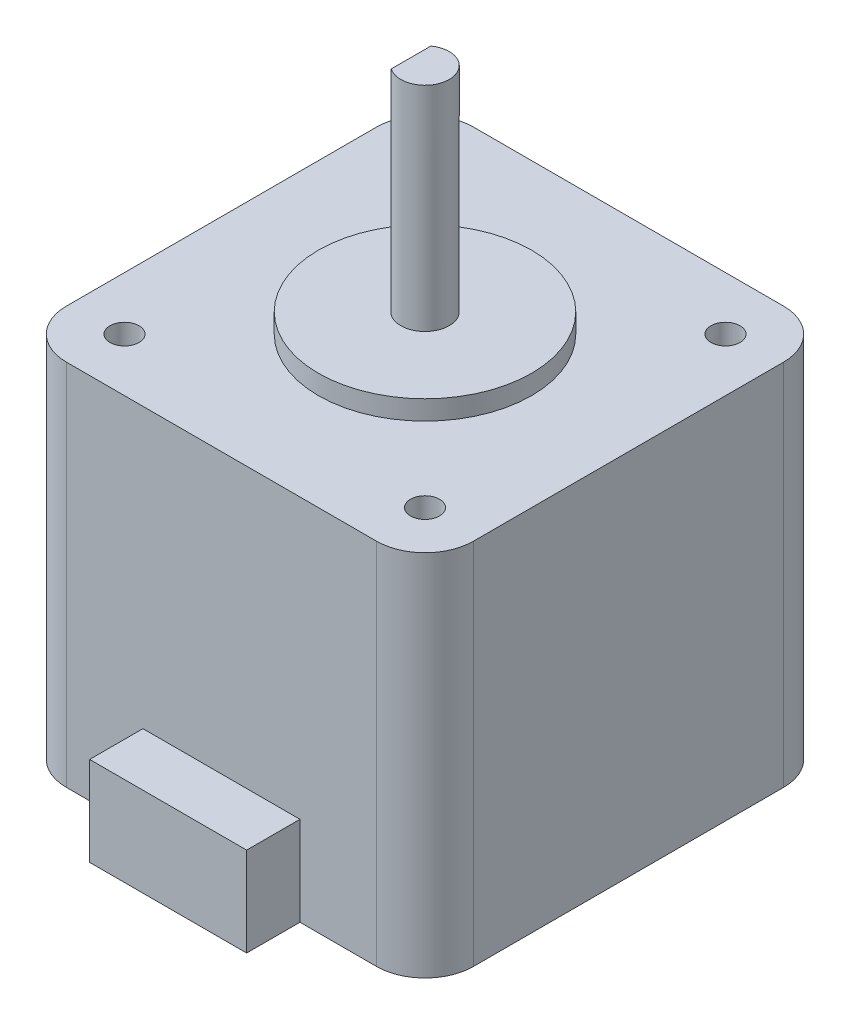
SolidWorks part; units mm, degrees
ref_plane "前视基准面" through (0, 0, 0) normal (0, 0, 1) x (1, 0, 0)
ref_plane "上视基准面" through (0, 0, 0) normal (0, 1, 0) x (1, 0, 0)
ref_plane "右视基准面" through (0, 0, 0) normal (1, 0, 0) x (0, 0, -1)
sketch "草图1" plane through (0, 0, 0) normal (0, 1, 0) x (1, 0, 0)
  line L1 (-21, 21) -> (21, 21)
  line L2 (-21, 21) -> (-21, -21)
  line L3 (-21, -21) -> (21, -21)
  line L4 (21, 21) -> (21, -21)
  line L5 (-21, 21) -> (21, -21) construction
  line L6 (-21, -21) -> (21, 21) construction
  point P0 (0, 0)
  dimension "D1" = 42
extrude "凸台-拉伸1" add sketch "草图1" along normal blind 38
sketch "草图2" plane through (0, 38, 0) normal (0, 1, 0) x (1, 0, 0)
  circle A0 centre (0, 0) radius 11
  dimension "D1" = 22
extrude "凸台-拉伸2" add sketch "草图2" along normal blind 2
sketch "草图3" plane through (0, 40, 0) normal (0, 1, 0) x (1, 0, 0)
  circle A0 centre (0, 0) radius 2.5
  dimension "D1" = 5
extrude "凸台-拉伸3" add sketch "草图3" along normal blind 22
sketch "草图5" plane through (0, 0, 21) normal (0, 0, 1) x (1, 0, 0)
  line L0 (-21, 0) -> (21, 0) construction
  line L1 (-8.1, 9.2) -> (8.1, 9.2)
  line L2 (-8.1, 9.2) -> (-8.1, 0)
  line L3 (-8.1, 0) -> (8.1, 0)
  line L4 (8.1, 9.2) -> (8.1, 0)
  line L5 (-8.1, 9.2) -> (8.1, 0) construction
  line L6 (-8.1, 0) -> (8.1, 9.2) construction
  point P0 (0, 4.6)
  point P5 (0, 0)
  dimension "D1" = 9.2
  dimension "D2" = 16.2
extrude "凸台-拉伸4" add sketch "草图5" along normal blind 5.5
sketch "草图6" plane through (0, 38, 0) normal (0, 1, 0) x (1, 0, 0)
  line L0 (-21, 21) -> (21, -21) construction
  line L1 (21, 21) -> (-21, -21) construction
  line L2 (0, 0) -> (40.1341, 0) construction
  circle A0 centre (-15.5, 15.5) radius 1.5
  circle A2 centre (15.5, 15.5) radius 1.5
  circle A3 centre (15.5, -15.5) radius 1.5
  circle A4 centre (-15.5, -15.5) radius 1.5
  point P23 (0, 0)
  dimension "D1" = 3
  dimension "D2" = 15.5
  dimension "D3" = 4
extrude "切除-拉伸1" cut sketch "草图6" against normal blind 5
fillet "圆角1" radius 5 4 edges at (21, 19, -21) (-21, 19, -21) (21, 19, 21) (-21, 19, 21)
sketch "草图7" plane through (0, 0, 0) normal (0, -1, 0) x (1, 0, 0)
  circle A0 centre (0, 0) radius 4
  dimension "D1" = 8
extrude "切除-拉伸2" cut sketch "草图7" against normal blind 5
sketch "草图8" plane through (0, 62, 0) normal (0, 1, 0) x (1, 0, 0)
  line L0 (-1.4382, 2.0449) -> (-1.4382, -2.0449)
  circle A0 centre (0, 0) radius 2.5 construction
  circle A1 centre (0, 0) radius 2.5 construction
  circle A2 centre (0, 0) radius 2.5
  circle M2 centre (0, 0) radius 2.5
extrude "切除-拉伸3" cut sketch "草图8" against normal blind 20 contours L0 M2
